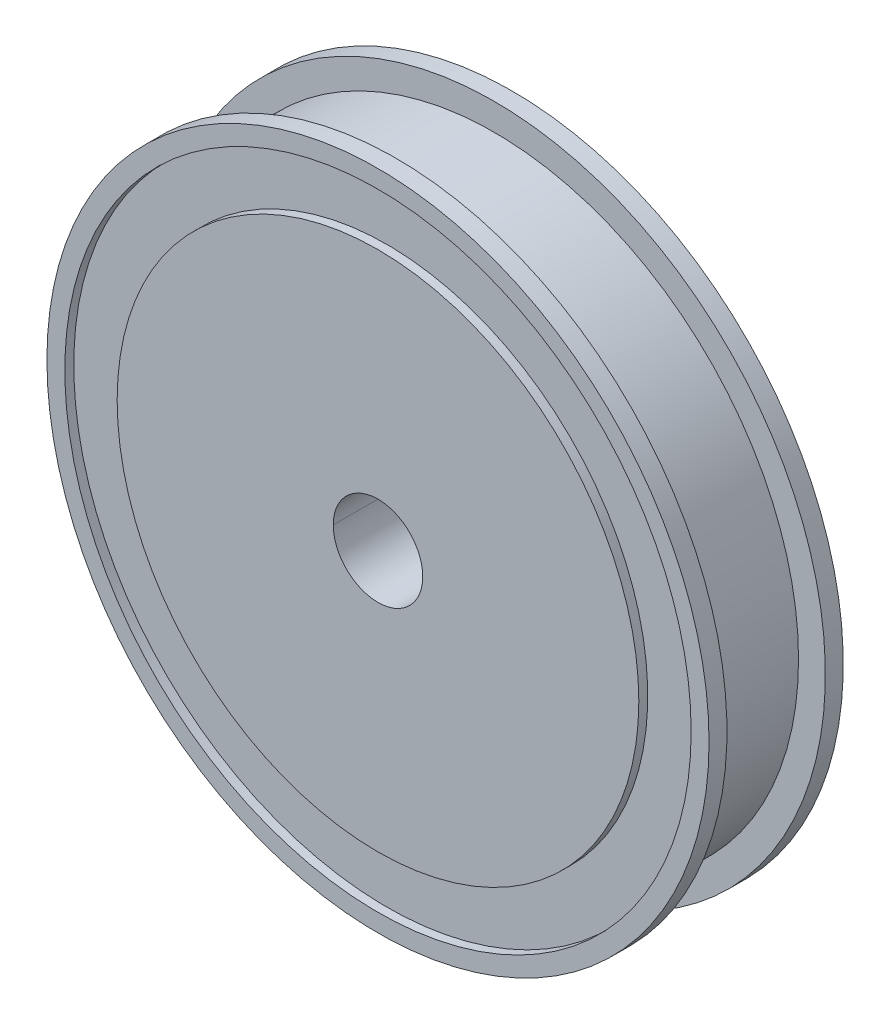
SolidWorks part; units mm, degrees
ref_plane "정면" through (0, 0, 0) normal (0, 0, 1) x (1, 0, 0)
ref_plane "윗면" through (0, 0, 0) normal (0, 1, 0) x (1, 0, 0)
ref_plane "우측면" through (0, 0, 0) normal (1, 0, 0) x (0, 0, -1)
sketch "스케치1" plane through (0, 0, 0) normal (0, 0, 1) x (1, 0, 0)
  circle A0 centre (0, 0) radius 29.15
  circle A1 centre (0, 0) radius 37
  circle A2 centre (0, 0) radius 35
  dimension "D1" = 74
  dimension "D2" = 58.3
  dimension "D3" = 2
extrude "보스-돌출1" add sketch "스케치1" along normal blind 1 contours A1 A2 | A0
sketch "스케치2" plane through (0, 0, 0) normal (0, 0, -1) x (-1, 0, 0)
  circle A0 centre (0, 0) radius 37
extrude "보스-돌출2" add sketch "스케치2" along normal blind 1
sketch "스케치3" plane through (0, 0, -1) normal (0, 0, -1) x (-1, 0, 0)
  circle A0 centre (0, 0) radius 34
  dimension "D1" = 68
extrude "보스-돌출3" add sketch "스케치3" along normal blind 11
sketch "스케치5" plane through (0, 0, -12) normal (0, 0, -1) x (-1, 0, 0)
  circle A0 centre (0, 0) radius 37
extrude "보스-돌출4" add sketch "스케치5" along normal blind 1
sketch "스케치4" plane through (0, 0, -13) normal (0, 0, -1) x (-1, 0, 0)
  circle A0 centre (0, 0) radius 37
  circle A1 centre (0, 0) radius 29.15
  circle A2 centre (0, 0) radius 35
  circle M4 centre (0, 0) radius 37
  dimension "D1" = 74
  dimension "D2" = 2
  dimension "D3" = 58.3
extrude "보스-돌출5" add sketch "스케치4" along normal blind 1 contours A2 M4 | A1
sketch "스케치6" plane through (0, 0, -14) normal (0, 0, -1) x (-1, 0, 0)
  circle A0 centre (0, 0) radius 5
  dimension "D1" = 10
extrude "컷-돌출1" cut sketch "스케치6" against normal through all
split line "분할선1"
